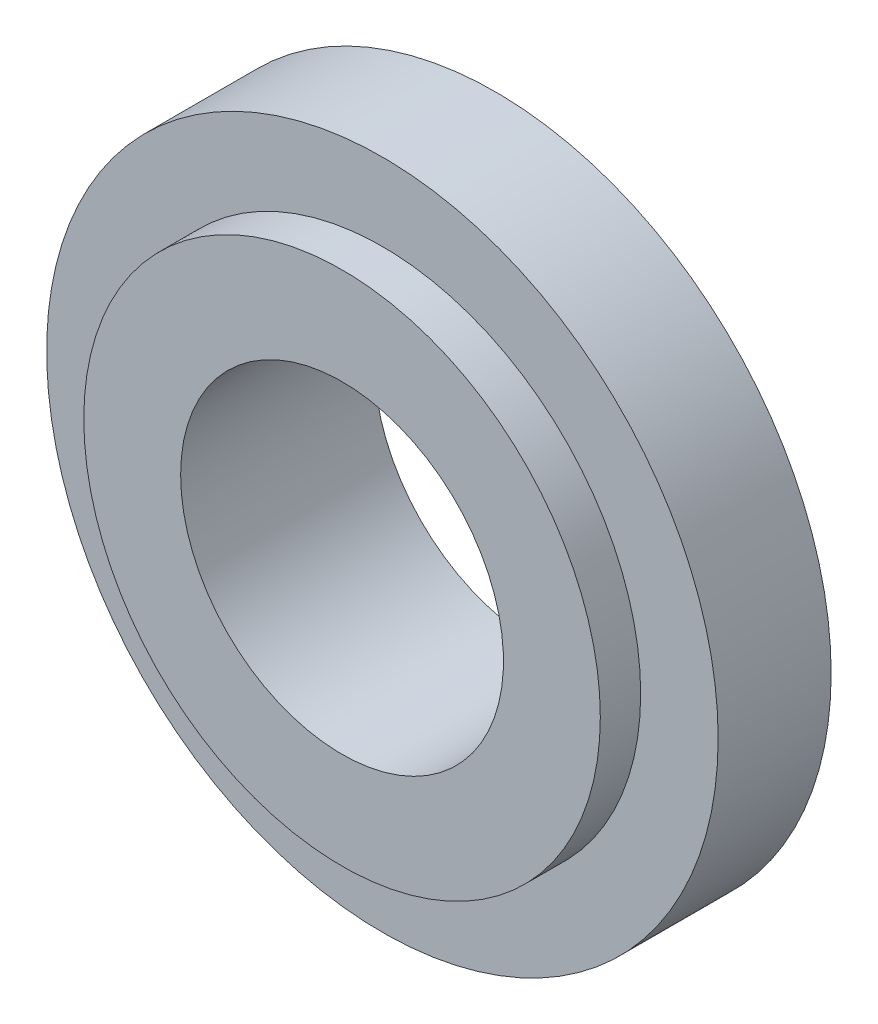
SolidWorks part; units mm, degrees
ref_plane "Front Plane" through (0, 0, 0) normal (0, 0, 1) x (1, 0, 0)
ref_plane "Top Plane" through (0, 0, 0) normal (0, 1, 0) x (1, 0, 0)
ref_plane "Right Plane" through (0, 0, 0) normal (1, 0, 0) x (0, 0, -1)
sketch "Sketch1" plane through (0, 0, 0) normal (0, 0, 1) x (1, 0, 0)
  circle A0 centre (0, 0) radius 7.9375
  circle A1 centre (0, 0) radius 12.7
  dimension "D1" = 15.875
  dimension "D2" = 25.4
extrude "Boss-Extrude1" add sketch "Sketch1" along normal blind 9.525
ref_plane "Plane1" through (0, 0, 4.7625) normal (0, 0, 1) x (1, 0, 0)
sketch "Sketch2" plane through (0, 0, 4.7625) normal (0, 0, 1) x (1, 0, 0)
  circle A0 centre (0, 0) radius 7.9375
  circle A1 centre (0, 0) radius 7.9375 construction
  circle A2 centre (0, 0) radius 16.51
  dimension "D1" = 33.02
extrude "Boss-Extrude2" add sketch "Sketch2" along normal mid plane 5.5562
